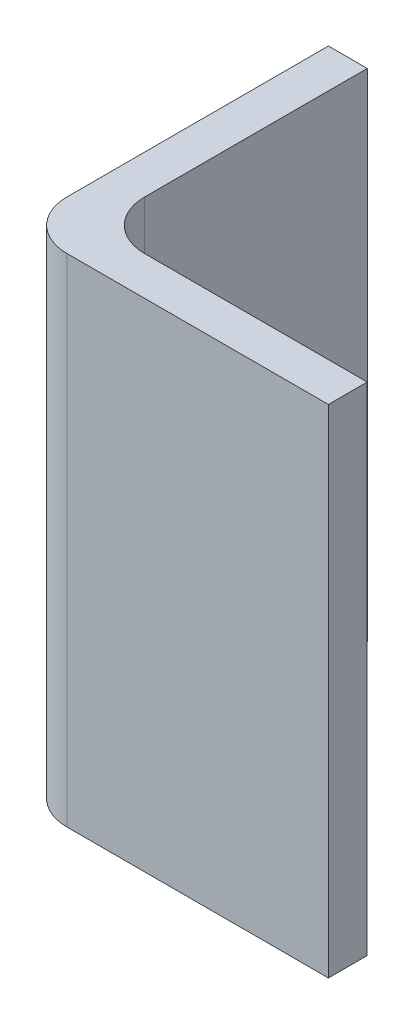
SolidWorks part; units mm, degrees
material "6061-T4 (SS)"
ref_plane "Front Plane" through (0, 0, 0) normal (0, 0, 1) x (1, 0, 0)
ref_plane "Top Plane" through (0, 0, 0) normal (0, 1, 0) x (1, 0, 0)
ref_plane "Right Plane" through (0, 0, 0) normal (1, 0, 0) x (0, 0, -1)
sketch "Sketch1" plane through (0, 0, 0) normal (0, 1, 0) x (1, 0, 0)
  line L1 (-7.9433, 9.7978) -> (-6.3533, 9.7978)
  line L2 (-7.9433, 9.7978) -> (-7.9433, -2.9022)
  line L3 (-7.9433, -2.9022) -> (-6.3533, -2.9022)
  line L4 (-6.3533, 9.7978) -> (-6.3533, -1.3147)
  line L5 (-6.3533, -2.9022) -> (4.7567, -2.9022)
  line L7 (-6.3533, -1.3147) -> (4.7567, -1.3147)
  line L8 (4.7567, -2.9022) -> (4.7567, -1.3147)
  point P7 (5.935, -2.2086)
  dimension "D1" = 1.5875
  dimension "D2" = 1.59
  dimension "D3" = 12.7
  dimension "D4" = 12.7
extrude "Boss-Extrude1" add sketch "Sketch1" along normal blind 20.32
fillet "Fillet1" radius 2 1 edges at (-6.3533, 10.16, 1.3147)
fillet "Fillet2" radius 2 1 edges at (-7.9433, 10.16, 2.9022)
